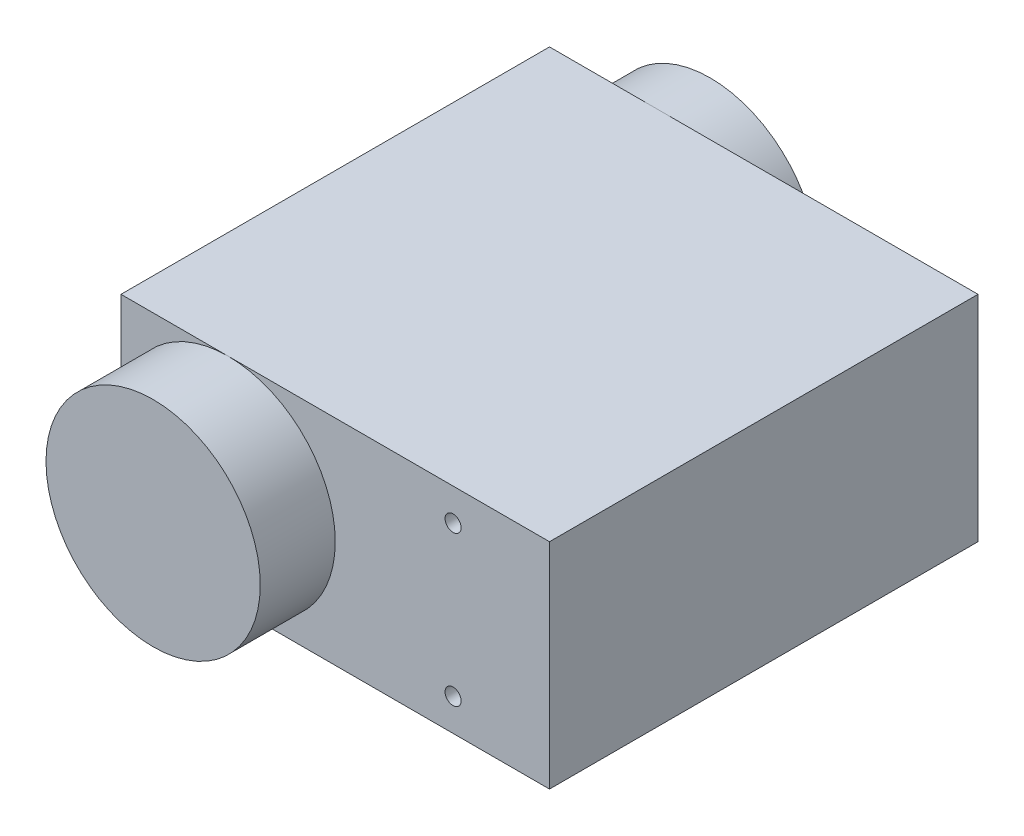
SolidWorks part; units mm, degrees
ref_plane "前视基准面" through (0, 0, 0) normal (0, 0, 1) x (1, 0, 0)
ref_plane "上视基准面" through (0, 0, 0) normal (0, 1, 0) x (1, 0, 0)
ref_plane "右视基准面" through (0, 0, 0) normal (1, 0, 0) x (0, 0, -1)
sketch "草图1" plane through (0, 0, 0) normal (0, 1, 0) x (1, 0, 0)
  line L1 (0, 0) -> (40, 0)
  line L2 (0, 0) -> (0, -40)
  line L3 (0, -40) -> (40, -40)
  line L4 (40, 0) -> (40, -40)
  dimension "D1" = 40
  dimension "D2" = 40
extrude "凸台-拉伸1" add sketch "草图1" along normal blind 20
sketch "草图2" plane through (0, 0, 40) normal (0, 0, 1) x (1, 0, 0)
  line L0 (0, 20) -> (40, 20) construction
  line L1 (0, 20) -> (0, 0) construction
  circle A0 centre (10, 10) radius 10
  dimension "D1" = 20
  dimension "D2" = 10
  dimension "D3" = 10
extrude "凸台-拉伸2" add sketch "草图2" along normal blind 7 and the other way blind 45
sketch "草图3" plane through (0, 0, 40) normal (0, 0, 1) x (1, 0, 0)
  line L0 (40, 20) -> (40, 0) construction
  line L1 (10, 20) -> (40, 20) construction
  line L2 (10, 0) -> (40, 0) construction
  circle A0 centre (31, 17) radius 0.75
  circle A1 centre (31, 3) radius 0.75
  dimension "D1" = 1.5
  dimension "D2" = 1.5
  dimension "D3" = 9
  dimension "D5" = 9
  dimension "D6" = 3
  dimension "D4" = 3
extrude "切除-拉伸1" cut sketch "草图3" against normal blind 3
